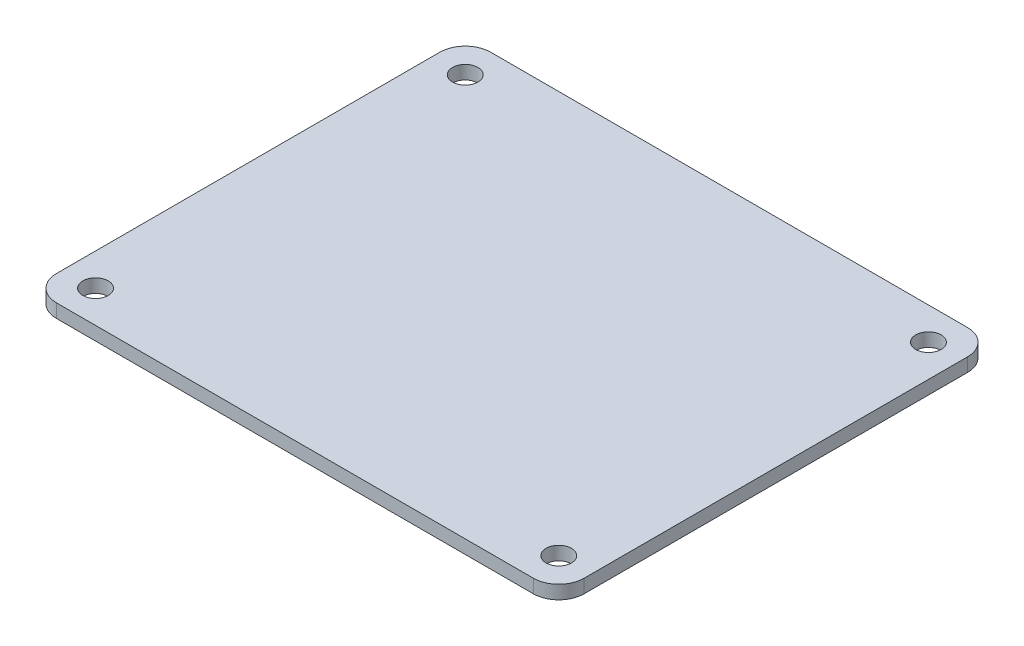
SolidWorks part; units mm, degrees
material "电源线路板"
ref_plane "前视基准面" through (0, 0, 0) normal (0, 0, 1) x (1, 0, 0)
ref_plane "上视基准面" through (0, 0, 0) normal (0, 1, 0) x (1, 0, 0)
ref_plane "右视基准面" through (0, 0, 0) normal (1, 0, 0) x (0, 0, -1)
other "Configuration Table"
sketch "草图1" plane through (0, 0, 0) normal (0, 1, 0) x (1, 0, 0)
  line L1 (-22.8574, 23.0021) -> (33.5026, 23.0021)
  line L2 (-25.8574, 20.0021) -> (-25.8574, -25.3079)
  line L3 (-22.8574, -28.3079) -> (33.5026, -28.3079)
  line L4 (36.5026, 20.0021) -> (36.5026, -25.3079)
  arc A0 (-25.8574, 20.0021) -> (-22.8574, 23.0021) centre (-22.8574, 20.0021) cw
  arc A1 (36.5026, 20.0021) -> (33.5026, 23.0021) centre (33.5026, 20.0021) ccw
  arc A2 (33.5026, -28.3079) -> (36.5026, -25.3079) centre (33.5026, -25.3079) ccw
  arc A3 (-25.8574, -25.3079) -> (-22.8574, -28.3079) centre (-22.8574, -25.3079) ccw
  circle A4 centre (-22.0474, 19.1921) radius 1.5
  circle A5 centre (32.6926, 19.1921) radius 1.5
  circle A6 centre (-22.0474, -24.4979) radius 1.5
  circle A7 centre (32.6926, -24.4979) radius 1.5
  point P6 (-25.8574, 23.0021)
  point P9 (36.5026, 23.0021)
  point P14 (-25.8574, -28.3079)
  dimension "D3" = 3
  dimension "D4" = 3
  dimension "D5" = 3
  dimension "D6" = 3
  dimension "D7" = 54.74
  dimension "D1" = 62.36
  dimension "D2" = 51.31
  dimension "D8" = 0
  dimension "D9" = 0
  dimension "D10" = 43.69
  dimension "D11" = 0
  dimension "D12" = 0
  dimension "D13" = 3.81
  dimension "D14" = 3.81
extrude "凸台-拉伸1" add sketch "草图1" along normal blind 1.6
